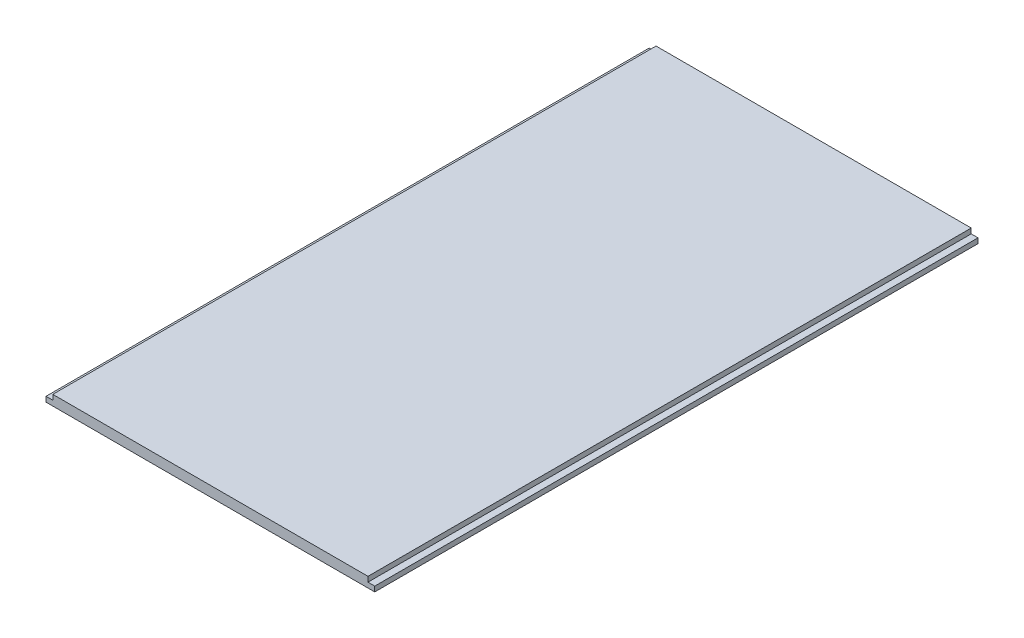
SolidWorks part; units mm, degrees
ref_plane "Front Plane" through (0, 0, 0) normal (0, 0, 1) x (1, 0, 0)
ref_plane "Top Plane" through (0, 0, 0) normal (0, 1, 0) x (1, 0, 0)
ref_plane "Right Plane" through (0, 0, 0) normal (1, 0, 0) x (0, 0, -1)
sketch "草图1" plane through (0, 0, 0) normal (0, 0, 1) x (1, 0, 0)
  line L0 (0, -49.7164) -> (0, 39.8128) construction
  line L1 (48.5, 0) -> (-48.5, 0)
  line L2 (-48.5, 0) -> (-48.5, 1.5)
  line L3 (-48.5, 1.5) -> (-46.5, 1.5)
  line L4 (-46.5, 1.5) -> (-46.5, 3)
  line L5 (-46.5, 3) -> (46.5, 3)
  line L6 (46.5, 1.5) -> (46.5, 3)
  line L7 (48.5, 1.5) -> (46.5, 1.5)
  line L8 (48.5, 0) -> (48.5, 1.5)
  point P10 (0, 3)
  point P13 (0, 0)
  dimension "D1" = 1.5
  dimension "D2" = 97
  dimension "D3" = 2
  dimension "D4" = 1.5
extrude "凸台-拉伸1" add sketch "草图1" along normal blind 178
